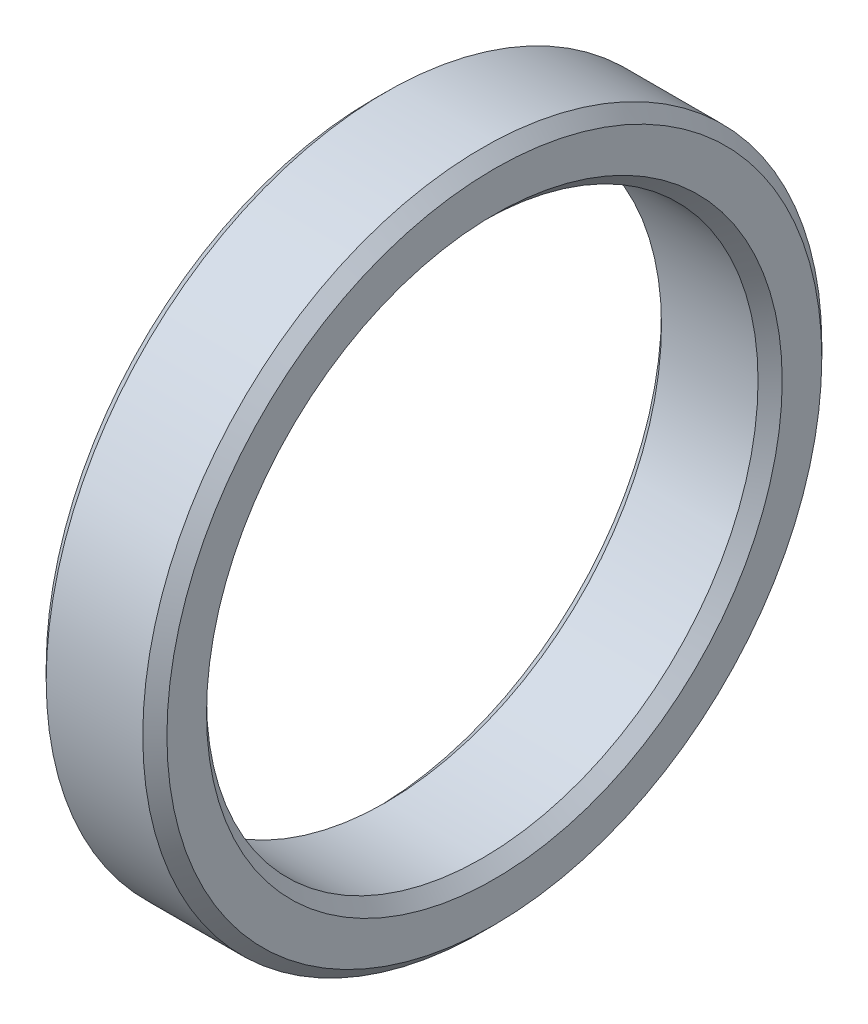
SolidWorks part; units mm, degrees
material "6061-T6 (SS)"
ref_plane "Front Plane" through (0, 0, 0) normal (0, 0, 1) x (1, 0, 0)
ref_plane "Top Plane" through (0, 0, 0) normal (0, 1, 0) x (1, 0, 0)
ref_plane "Right Plane" through (0, 0, 0) normal (1, 0, 0) x (0, 0, -1)
ref_axis "Axis1" through (-88.99, 0, 0) along (1, 0, 0)
sketch "Sketch1" plane through (0, 0, 0) normal (0, 0, 1) x (1, 0, 0)
  line L0 (0, 0) -> (12.7, 0) construction
  line L1 (-88.99, 0) -> (88.99, 0) construction
  line L2 (0, -29.0132) -> (0, 29.0132) construction
  line L3 (0, 29.0132) -> (0, 35.7188)
  line L4 (0, 35.7188) -> (12.7, 35.7188)
  line L5 (12.7, 35.7188) -> (12.7, 29.0132)
  line L6 (12.7, 29.0132) -> (12.7, -29.0132) construction
  line L7 (0, 29.0132) -> (12.7, 29.0132)
  line L8 (0, -29.0132) -> (12.7, -29.0132) construction
  line L9 (12.7, -35.7188) -> (12.7, -29.0132) construction
  line L10 (0, -35.7188) -> (12.7, -35.7188) construction
  line L11 (0, -29.0132) -> (0, -35.7188) construction
  dimension "D1" = 71.4375
  dimension "D2" = 6.7056
  dimension "D3" = 12.7
revolve "Revolve1" add sketch "Sketch1" angle 360 about axis through (-88.99, 0, 0) along (1, 0, 0)
chamfer "Chamfer1" distance 1.27 angle 45 4 edges at (0, 0, 29.0132) (0, 0, 35.7188) (12.7, 0, 29.0132) (12.7, 0, 35.7188)
